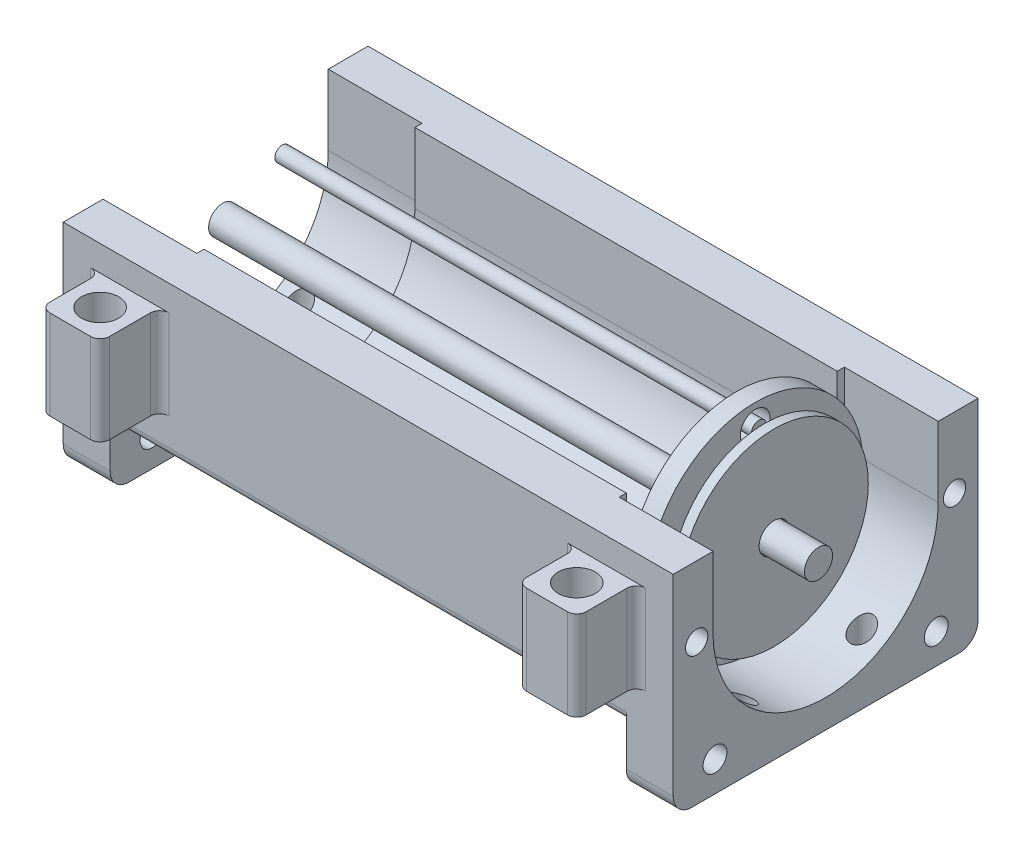
SolidWorks part; units mm, degrees
ref_plane "Front Plane" through (0, 0, 0) normal (0, 0, 1) x (1, 0, 0)
ref_plane "Top Plane" through (0, 0, 0) normal (0, 1, 0) x (1, 0, 0)
ref_plane "Right Plane" through (0, 0, 0) normal (1, 0, 0) x (0, 0, -1)
sketch "Sketch1" plane through (0, 0, 0) normal (1, 0, 0) x (0, 0, -1)
  line L0 (-22.4812, 0) -> (-22.4812, 15)
  line L1 (22.4812, 0) -> (22.4812, 15)
  line L2 (-23.3122, -17.371) -> (-30.4812, -17.371)
  line L3 (0, 0) -> (0, 31.7138) construction
  line L4 (-15.3123, -30) -> (15.4297, -30)
  line L5 (-17.3123, -23.371) -> (-17.3123, -28)
  line L6 (17.4297, -23.371) -> (17.4297, -28)
  line L7 (23.4297, -17.371) -> (30.0587, -17.371)
  line L8 (-32.4812, 15) -> (-32.4812, -15.371)
  line L9 (22.4812, 15) -> (32.4812, 15)
  line L10 (-22.4812, 15) -> (-32.4812, 15)
  line L11 (32.4812, 15) -> (32.4813, -15.371)
  line L13 (30.4812, -17.371) -> (30.0587, -17.371)
  line L14 (-27.4812, 15) -> (-27.4813, 0) construction
  line L15 (27.4812, 15) -> (27.4812, 0) construction
  arc A0 (-22.4812, 0) -> (22.4812, 0) centre (0, 0) ccw
  arc A1 (-23.3122, -17.371) -> (-17.3123, -23.371) centre (-23.3122, -23.371) cw
  arc A2 (17.4297, -23.371) -> (23.4297, -17.371) centre (23.4297, -23.371) cw
  arc A3 (-30.4812, -17.371) -> (-32.4812, -15.371) centre (-30.4812, -15.371) cw
  arc A4 (32.4813, -15.371) -> (30.4812, -17.371) centre (30.4812, -15.371) cw
  arc A5 (-17.3123, -28) -> (-15.3123, -30) centre (-15.3123, -28) ccw
  arc A6 (17.4297, -28) -> (15.4297, -30) centre (15.4297, -28) cw
  circle A7 centre (0, 0) radius 27.4813 construction
  circle A8 centre (-27.4813, 0) radius 2.3813
  circle A9 centre (27.4812, 0) radius 2.3813
  dimension "D1" = 6
  dimension "D2" = 6
  dimension "D3" = 2
  dimension "D4" = 2
  dimension "D5" = 2
  dimension "D6" = 10
  dimension "D7" = 54.9625
  dimension "D8" = 4.7625
extrude "Boss-Extrude1" add sketch "Sketch1" along normal mid plane 90
ref_plane "Plane1" through (45, 0, 0) normal (1, 0, 0) x (0, 0, -1)
ref_plane "Plane2" through (46, 0, 0) normal (1, 0, 0) x (0, 0, -1)
sketch "Sketch3" plane through (46, 0, 0) normal (1, 0, 0) x (0, 0, -1)
  line L0 (0, 0) -> (0, 1.0694) construction
  circle A0 centre (0, 0) radius 3.175
  circle A1 centre (0, 18.5125) radius 1.5875 construction
  circle A2 centre (0, 18.5125) radius 3.175
  circle A3 centre (0, 0) radius 23
  circle A4 centre (-18.5125, 0) radius 1.5875 construction
  circle A5 centre (-18.5125, 0) radius 3.175
  circle A6 centre (0, -18.5125) radius 1.5875 construction
  circle A7 centre (0, -18.5125) radius 3.175
  circle A8 centre (18.5125, 0) radius 1.5875 construction
  circle A9 centre (18.5125, 0) radius 3.175
  circle A10 centre (0, 0) radius 20.1 construction
  circle A11 centre (0, 0) radius 18.5125 construction
  dimension "D1" = 6.35
  dimension "D2" = 3.175
  dimension "D3" = 6.35
  dimension "D4" = 46
  dimension "D5" = 40.2
  dimension "D6" = 37.025
extrude "Boss-Extrude2" add sketch "Sketch3" along normal blind 4 separate body
ref_plane "Sketch16" through (52, 0, 0) normal (1, 0, 0) x (0, 0, -1)
sketch "Sketch17" plane through (52, 0, 0) normal (1, 0, 0) x (0, 0, -1)
  circle A1 centre (0, 0) radius 3.175
  circle A2 centre (0, 0) radius 20.1
  dimension "D1" = 6.35
extrude "Boss-Extrude4" add sketch "Sketch17" along normal blind 2 separate body
sketch "Sketch19" plane through (0, 0, 0) normal (1, 0, 0) x (0, 0, -1)
  circle A0 centre (0, 0) radius 3
  circle A1 centre (0, 0) radius 18.5125 construction
  dimension "D1" = 37.025
  dimension "D2" = 6
extrude "Boss-Extrude6" add sketch "Sketch19" along normal mid plane 127
sketch "Sketch20" plane through (0, 0, 0) normal (1, 0, 0) x (0, 0, -1)
  circle A0 centre (0, 0) radius 18.5125 construction
  circle A1 centre (0, 18.5125) radius 1.5875
  circle A2 centre (18.5125, 0) radius 1.5875
  circle A3 centre (0, -18.5125) radius 1.5875
  circle A4 centre (-18.5125, 0) radius 1.5875
  dimension "D1" = 37.025
  dimension "D2" = 3.175
extrude "Boss-Extrude7" add sketch "Sketch20" along normal mid plane 101.6 separate body
sketch "Sketch21" plane through (45, 0, 0) normal (1, 0, 0) x (0, 0, -1)
  line L0 (-24, 0) -> (-24, 15)
  line L1 (24, 0) -> (24, 15)
  line L2 (-23.3122, -17.371) -> (-30.4812, -17.371)
  line L3 (0, 0) -> (0, 31.7138) construction
  line L4 (-15.3123, -30) -> (15.4297, -30)
  line L5 (-17.3123, -23.371) -> (-17.3123, -28)
  line L6 (17.4297, -23.371) -> (17.4297, -28)
  line L7 (23.4297, -17.371) -> (30.0587, -17.371)
  line L8 (-32.4812, 15) -> (-32.4812, -15.371)
  line L9 (24, 15) -> (32.4812, 15)
  line L10 (-24, 15) -> (-32.4812, 15)
  line L11 (32.4812, 15) -> (32.4813, -15.371)
  line L12 (-24, 0) -> (24, 0) construction
  line L13 (30.4812, -17.371) -> (30.0587, -17.371)
  line L14 (0, 0) -> (0, -24) construction
  arc A0 (-24, 0) -> (24, 0) centre (0, 0) ccw
  arc A1 (-23.3122, -17.371) -> (-17.3123, -23.371) centre (-23.3122, -23.371) cw
  arc A2 (17.4297, -23.371) -> (23.4297, -17.371) centre (23.4297, -23.371) cw
  arc A3 (-30.4812, -17.371) -> (-32.4812, -15.371) centre (-30.4812, -15.371) cw
  arc A4 (32.4813, -15.371) -> (30.4812, -17.371) centre (30.4812, -15.371) cw
  arc A5 (-17.3123, -28) -> (-15.3123, -30) centre (-15.3123, -28) ccw
  arc A6 (17.4297, -28) -> (15.4297, -30) centre (15.4297, -28) cw
  circle A7 centre (0, 0) radius 23 construction
  circle A8 centre (0, 0) radius 27.4812 construction
  circle A9 centre (-27.4813, 0) radius 2.3813
  circle A10 centre (27.4812, 0) radius 2.3812
  dimension "D1" = 6
  dimension "D2" = 6
  dimension "D3" = 2
  dimension "D4" = 2
  dimension "D5" = 2
  dimension "D6" = 54.9625
  dimension "D7" = 46
extrude "Boss-Extrude8" add sketch "Sketch21" along normal blind 10
ref_plane "Plane5" through (55, 0, 0) normal (1, 0, 0) x (0, 0, -1)
sketch "Sketch23" plane through (55, 0, 0) normal (1, 0, 0) x (0, 0, -1)
  line L0 (-24, 0) -> (-24, 15)
  line L1 (24, 0) -> (24, 15)
  line L2 (32.4812, 15) -> (24, 15)
  line L4 (-28.4812, -30) -> (28.4812, -30)
  line L8 (-32.4812, 15) -> (-32.4813, -26)
  line L10 (-24, 15) -> (-32.4812, 15)
  line L11 (32.4812, 15) -> (32.4813, -26)
  arc A0 (-24, 0) -> (24, 0) centre (0, 0) ccw
  arc A1 (28.4812, -30) -> (32.4813, -26) centre (28.4813, -26) ccw
  circle A2 centre (0, 0) radius 23.5712 construction
  arc A3 (-28.4812, -30) -> (-32.4813, -26) centre (-28.4813, -26) cw
  circle A4 centre (-23.5712, -23.5712) radius 2.54
  circle A5 centre (23.5712, -23.5712) radius 2.54
  circle A7 centre (-27.4813, 0) radius 2.3813
  circle A8 centre (27.4812, 0) radius 2.3812
  circle A9 centre (0, 0) radius 22.4812 construction
  dimension "D1" = 47.1424
  dimension "D2" = 4
  dimension "D3" = 4
  dimension "D7" = 44.9625
extrude "Boss-Extrude9" add sketch "Sketch23" along normal blind 10
ref_plane "Plane6" through (0, -30, 0) normal (0, -1, 0) x (1, 0, 0)
sketch "Sketch24" plane through (0, -30, 0) normal (0, -1, 0) x (1, 0, 0)
  line L0 (55, 0) -> (65, 0) construction
  line L1 (55, -24.75) -> (55, 24.75) construction
  line L2 (65, 28.4812) -> (65, -28.4812) construction
  line L3 (60, 12.7) -> (60, -12.7) construction
  circle A0 centre (60, 0) radius 12.7 construction
  circle A1 centre (60, 12.7) radius 2.3812
  circle A2 centre (60, -12.7) radius 2.3812
  dimension "D1" = 25.4
  dimension "D2" = 4.7625
extrude "Cut-Extrude1" cut sketch "Sketch24" against normal blind 50 contours A2 | A1
ref_plane "Plane7" through (-45, 0, 0) normal (-1, 0, 0) x (0, 0, 1)
sketch "Sketch25" plane through (-45, 0, 0) normal (-1, 0, 0) x (0, 0, 1)
  line L0 (-24, 0) -> (-24, 15)
  line L1 (24, 0) -> (24, 15)
  line L2 (-23.3122, -17.371) -> (-30.4812, -17.371)
  line L3 (0, 0) -> (0, 31.7138) construction
  line L4 (-15.3123, -30) -> (15.4297, -30)
  line L5 (-17.3123, -23.371) -> (-17.3123, -28)
  line L6 (17.4297, -23.371) -> (17.4297, -28)
  line L7 (23.4297, -17.371) -> (30.0587, -17.371)
  line L8 (-32.4812, 15) -> (-32.4812, -15.371)
  line L9 (24, 15) -> (32.4812, 15)
  line L10 (-24, 15) -> (-32.4812, 15)
  line L11 (32.4812, 15) -> (32.4813, -15.371)
  line L12 (-24, 0) -> (24, 0) construction
  line L13 (30.4812, -17.371) -> (30.0587, -17.371)
  line L14 (0, 0) -> (0, -24) construction
  arc A0 (-24, 0) -> (24, 0) centre (0, 0) ccw
  arc A1 (-23.3122, -17.371) -> (-17.3123, -23.371) centre (-23.3122, -23.371) cw
  arc A2 (17.4297, -23.371) -> (23.4297, -17.371) centre (23.4297, -23.371) cw
  arc A3 (-30.4812, -17.371) -> (-32.4812, -15.371) centre (-30.4812, -15.371) cw
  arc A4 (32.4813, -15.371) -> (30.4812, -17.371) centre (30.4812, -15.371) cw
  arc A5 (-17.3123, -28) -> (-15.3123, -30) centre (-15.3123, -28) ccw
  arc A6 (17.4297, -28) -> (15.4297, -30) centre (15.4297, -28) cw
  circle A7 centre (0, 0) radius 23 construction
  circle A8 centre (-27.4812, 0) radius 2.3813
  circle A9 centre (27.4813, 0) radius 2.3813
  dimension "D1" = 6
  dimension "D2" = 6
  dimension "D3" = 2
  dimension "D4" = 2
  dimension "D5" = 2
  dimension "D7" = 46
extrude "Boss-Extrude10" add sketch "Sketch25" along normal blind 10
ref_plane "Plane8" through (-55, 0, 0) normal (-1, 0, 0) x (0, 0, 1)
sketch "Sketch27" plane through (-55, 0, 0) normal (-1, 0, 0) x (0, 0, 1)
  line L0 (-24, 0) -> (-24, 15)
  line L1 (24, 0) -> (24, 15)
  line L3 (0, 0) -> (0, 31.7138) construction
  line L4 (-28.4812, -30) -> (28.4812, -30)
  line L8 (-32.4812, 15) -> (-32.4813, -26)
  line L9 (24, 15) -> (32.4812, 15)
  line L10 (-24, 15) -> (-32.4812, 15)
  line L11 (32.4812, 15) -> (32.4813, -26)
  arc A0 (-24, 0) -> (24, 0) centre (0, 0) ccw
  arc A1 (-32.4813, -26) -> (-28.4812, -30) centre (-28.4813, -26) ccw
  arc A2 (28.4812, -30) -> (32.4813, -26) centre (28.4813, -26) ccw
  circle A3 centre (0, 0) radius 23.5712 construction
  circle A4 centre (-23.5712, -23.5712) radius 2.54
  circle A5 centre (23.5712, -23.5712) radius 2.54
  circle A7 centre (-27.4812, 0) radius 2.3813
  circle A8 centre (27.4813, 0) radius 2.3813
  dimension "D1" = 4
  dimension "D2" = 4
  dimension "D3" = 47.1424
extrude "Boss-Extrude11" add sketch "Sketch27" along normal blind 10
mirror "Mirror6" about plane through (0, 0, 0) normal (1, 0, 0) of "Cut-Extrude1"
ref_plane "Plane9" through (0, 0, 32.4812) normal (0, 0, 1) x (1, 0, 0)
ref_plane "Plane10" through (0, 15, 0) normal (0, 1, 0) x (-1, 0, 0)
sketch "Sketch29" plane through (0, 0, 32.4812) normal (0, 0, 1) x (1, 0, 0)
  line L0 (63, 9.3126) -> (-63, 9.525) construction
  line L2 (63, -9.525) -> (-63, -9.525) construction
  line L4 (44.45, 9.525) -> (44.45, -9.525) construction
  line L5 (-63, 9.525) -> (63, 9.525)
  line L6 (-63, 9.525) -> (-63, -9.525)
  line L7 (-63, -9.525) -> (63, -9.525)
  line L8 (63, 9.525) -> (63, -9.525)
  line L9 (57.15, 9.525) -> (57.15, -9.525) construction
  line L11 (44.45, 9.525) -> (57.15, 9.525)
  line L12 (44.45, 9.525) -> (44.45, -9.525)
  line L13 (44.45, -9.525) -> (57.15, -9.525)
  line L14 (57.15, 9.525) -> (57.15, -9.525)
  circle A0 centre (0, 0) radius 50.8 construction
  circle A1 centre (50.8, 0) radius 6.35 construction
  dimension "D1" = 12.7
  dimension "D2" = 19.05
extrude "Boss-Extrude12" add sketch "Sketch29" along normal blind 12.7 contours L14 L5 L12 L7
sketch "Sketch30" plane through (0, 9.525, 0) normal (0, 1, 0) x (1, 0, 0)
  circle A0 centre (50.8, -38.8312) radius 3.9687
  dimension "D1" = 7.9375
extrude "Cut-Extrude2" cut sketch "Sketch30" against normal blind 40
mirror "Mirror7" about plane through (0, 0, 0) normal (1, 0, 0) of "Cut-Extrude2", "Boss-Extrude12"
fillet "Fillet1" radius 2 8 edges at (57.15, 0, 45.1812) (57.15, 0, 32.4812) (44.45, 0, 45.1812) (44.45, 0, 32.4812) (-57.15, 0, 45.1812) (-57.15, 0, 32.4812) (-44.45, 0, 45.1812) (-44.45, 0, 32.4812)
